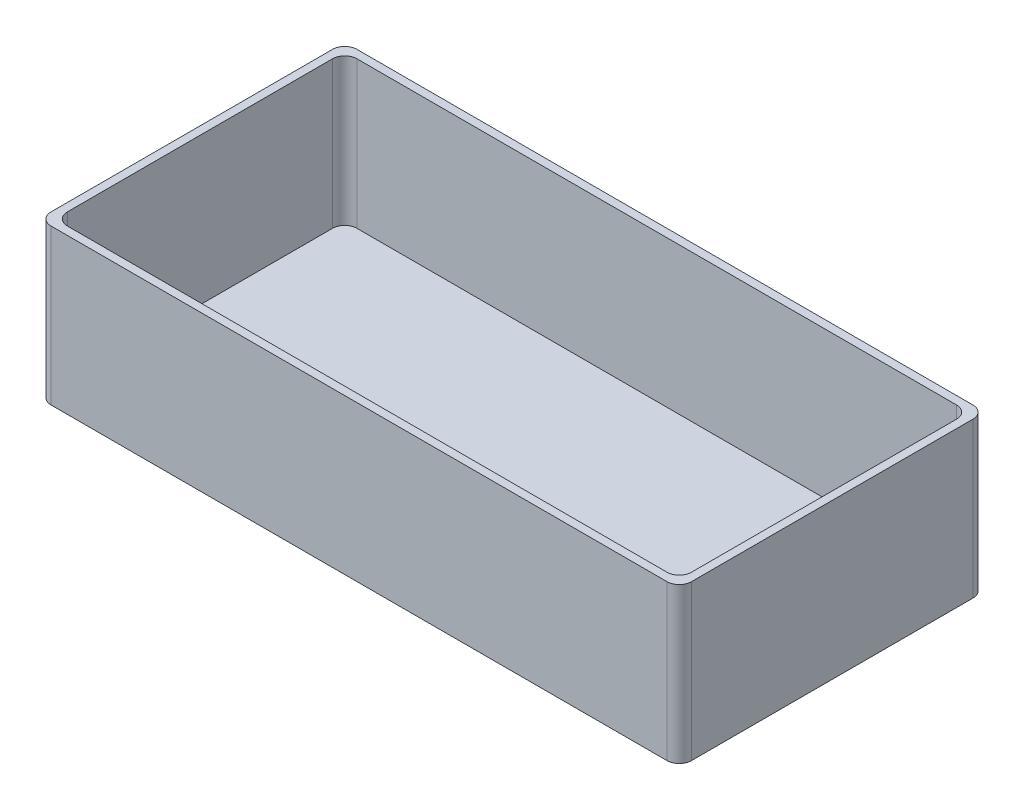
SolidWorks part; units mm, degrees
ref_plane "Front Plane" through (0, 0, 0) normal (0, 0, 1) x (1, 0, 0)
ref_plane "Top Plane" through (0, 0, 0) normal (0, 1, 0) x (1, 0, 0)
ref_plane "Right Plane" through (0, 0, 0) normal (1, 0, 0) x (0, 0, -1)
sketch "Sketch1" plane through (0, 0, 0) normal (0, 1, 0) x (1, 0, 0)
  line L1 (0, 0) -> (-157, 0)
  line L2 (0, 0) -> (0, 75)
  line L3 (0, 75) -> (-157, 75)
  line L4 (-157, 0) -> (-157, 75)
  dimension "D1" = 157
  dimension "D2" = 75
extrude "Boss-Extrude1" add sketch "Sketch1" along normal blind 38
shell "Shell1" thickness 2
fillet "Fillet1" radius 3 8 edges at (-2, 20, -2) (0, 19, 0) (-2, 20, -73) (0, 19, -75) (-155, 20, -73) (-157, 19, -75) (-157, 19, 0) (-155, 20, -2)
